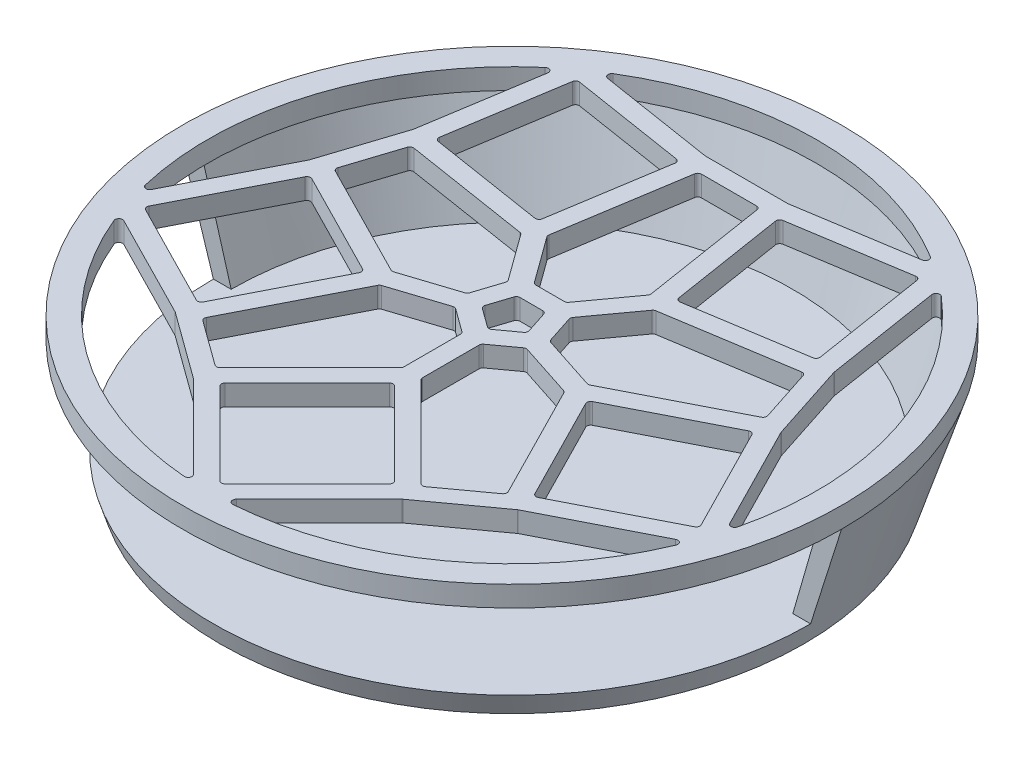
SolidWorks part; units mm, degrees
ref_plane "Plan de face" through (0, 0, 0) normal (0, 0, 1) x (1, 0, 0)
ref_plane "Plan de dessus" through (0, 0, 0) normal (0, 1, 0) x (1, 0, 0)
ref_plane "Plan de droite" through (0, 0, 0) normal (1, 0, 0) x (0, 0, -1)
ref_plane "Plan2" through (0, 2.75, 0) normal (0, 1, 0) x (1, 0, 0)
ref_plane "Plan3" through (0, 15.75, 0) normal (0, 1, 0) x (1, 0, 0)
sketch "Esquisse4" plane through (0, 0, 0) normal (0, 0, 1) x (1, 0, 0)
  line L0 (0, 0) -> (-39, 0)
  line L1 (-39, 0) -> (-44, 15.75)
  line L4 (-44, 15.75) -> (-44, 18.5)
  line L5 (-44, 18.5) -> (0, 18.5)
  line L7 (0, 0) -> (0, 18.5)
  dimension "D1" = 44
  dimension "D2" = 39
  dimension "D3" = 2.75
  dimension "D4" = 18.5
revolve "Révolution1" add sketch "Esquisse4" angle 360 about L7
sketch "Esquisse5" plane through (0, 2.75, 0) normal (0, 1, 0) x (1, 0, 0)
  line L8 (44, -44) -> (-44, -44)
  line L9 (37.5, 0) -> (44, 0)
  line L10 (44, 0) -> (44, -44)
  line L11 (-37.5, 0) -> (-44, 0)
  line L12 (-44, 0) -> (-44, -44)
  arc A0 (37.5, 0) -> (-37.5, 0) centre (0, 0) ccw
  circle A3 centre (0, 0) radius 44 construction
  dimension "D3" = 37.5
sketch "Esquisse6" plane through (0, 15.75, 0) normal (0, 1, 0) x (1, 0, 0)
  line L1 (-44, -44) -> (44, -44)
  line L3 (-41.25, 0) -> (-44, 0)
  line L4 (-44, 0) -> (-44, -44)
  line L5 (41.25, 0) -> (44, 0)
  line L6 (44, 0) -> (44, -44)
  arc A0 (41.25, 0) -> (-41.25, 0) centre (0, 0) ccw
  circle A1 centre (0, 0) radius 44 construction
  circle A2 centre (0, 0) radius 44 construction
  dimension "D3" = 41.25
loft "Enlèvement de matière-Lissage2" cut profiles "Esquisse5", "Esquisse6"
sketch "Esquisse7" plane through (0, 18.5, 0) normal (0, 1, 0) x (1, 0, 0)
  line L0 (0, -15.6655) -> (-11.6673, -27.3327)
  line L15 (-11.6673, -27.3327) -> (0, -39)
  line L16 (0, -39) -> (11.6673, -27.3327)
  line L17 (11.6673, -27.3327) -> (0, -15.6655)
  line L18 (0, -39) -> (0, -15.6655) construction
  line L19 (-11.6673, -27.3327) -> (11.6673, -27.3327) construction
  line L20 (-29.6004, 2.6499) -> (-37.0912, -12.0517)
  line L21 (-37.0912, -12.0517) -> (-22.3896, -19.5425)
  line L22 (-22.3896, -19.5425) -> (-14.8988, -4.8409)
  line L23 (-14.8988, -4.8409) -> (-29.6004, 2.6499)
  line L24 (-6.6268, 28.9705) -> (-22.9236, 31.5517)
  line L25 (-22.9236, 31.5517) -> (-25.5048, 15.2548)
  line L26 (-25.5048, 15.2548) -> (-9.2079, 12.6736)
  line L27 (-9.2079, 12.6736) -> (-6.6268, 28.9705)
  line L28 (25.5048, 15.2548) -> (22.9236, 31.5517)
  line L29 (22.9236, 31.5517) -> (6.6268, 28.9705)
  line L30 (6.6268, 28.9705) -> (9.2079, 12.6736)
  line L31 (9.2079, 12.6736) -> (25.5048, 15.2548)
  line L32 (22.3896, -19.5425) -> (37.0912, -12.0517)
  line L33 (37.0912, -12.0517) -> (29.6004, 2.6499)
  line L34 (29.6004, 2.6499) -> (14.8988, -4.8409)
  line L35 (14.8988, -4.8409) -> (22.3896, -19.5425)
  line L36 (0, 0) -> (0, -44) construction
  circle A0 centre (0, 0) radius 44 construction
  point P28 (0, 0)
  dimension "D2" = 5
  dimension "D1" = 16.5
extrude "Enlèv. mat.-Extru.3" cut sketch "Esquisse7" against normal up to next
sketch "Esquisse8" plane through (0, 18.5, 0) normal (0, 1, 0) x (1, 0, 0)
  line L2 (-20.3418, -21.0303) -> (-12.3388, -5.3235)
  line L3 (-12.3388, -5.3235) -> (-4.7304, -2.8513)
  line L17 (-26.287, 12.8475) -> (-8.8758, 10.0899)
  line L18 (-1.25, -5.3799) -> (-1.25, -13.3799)
  line L19 (-1.25, -13.3799) -> (-13.715, -25.845)
  line L20 (-13.715, -25.845) -> (-20.3418, -21.0303)
  line L21 (-13.1114, -2.9458) -> (-28.8182, 5.0572)
  line L22 (-28.8182, 5.0572) -> (-26.287, 12.8475)
  line L23 (-8.8758, 10.0899) -> (-4.1735, 3.6177)
  line L24 (-5.5029, -0.4737) -> (-13.1114, -2.9458)
  line L25 (4.0956, 28.9705) -> (6.8533, 11.5593)
  line L26 (-6.8533, 11.5593) -> (-4.0956, 28.9705)
  line L27 (-4.0956, 28.9705) -> (4.0956, 28.9705)
  line L28 (6.8533, 11.5593) -> (2.151, 5.0872)
  line L29 (-2.151, 5.0872) -> (-6.8533, 11.5593)
  line L31 (28.8182, 5.0572) -> (13.1114, -2.9458)
  line L41 (8.8758, 10.0899) -> (26.287, 12.8475)
  line L42 (2.151, 5.0872) -> (-2.151, 5.0872)
  line L43 (0, -15.6655) -> (-11.6673, -27.3327) construction
  line L44 (26.287, 12.8475) -> (28.8182, 5.0572)
  line L45 (13.1114, -2.9458) -> (5.5029, -0.4737)
  line L46 (4.1735, 3.6177) -> (8.8758, 10.0899)
  line L47 (13.715, -25.845) -> (1.25, -13.3799)
  line L48 (12.3388, -5.3235) -> (20.3418, -21.0303)
  line L49 (20.3418, -21.0303) -> (13.715, -25.845)
  line L50 (1.25, -13.3799) -> (1.25, -5.3799)
  line L51 (4.7304, -2.8513) -> (12.3388, -5.3235)
  line L52 (-22.3896, -19.5425) -> (-14.8988, -4.8409) construction
  line L53 (5.5029, -0.4737) -> (4.1735, 3.6177)
  line L54 (-22.3072, 33.9852) -> (-5.5125, 31.3252)
  line L55 (-5.5125, 31.3252) -> (5.5125, 31.3252)
  line L56 (5.5125, 31.3252) -> (22.3072, 33.9852)
  line L57 (-6.6268, 28.9705) -> (-22.9236, 31.5517) construction
  line L58 (22.9236, 31.5517) -> (6.6268, 28.9705) construction
  line L59 (0, 28.9705) -> (0, 30.6305) construction
  line L60 (-8.8758, 10.0899) -> (-5.5125, 31.3252) construction
  line L61 (-9.2079, 12.6736) -> (-6.6268, 28.9705) construction
  line L62 (31.4955, 4.4373) -> (39.2151, -10.7134)
  line L63 (25.4285, 31.7174) -> (28.0886, 14.9227)
  line L64 (28.0886, 14.9227) -> (31.4955, 4.4373)
  line L65 (13.9528, -28.5827) -> (1.9291, -40.6064)
  line L66 (38.0229, -14.3828) -> (22.8721, -22.1024)
  line L67 (22.8721, -22.1024) -> (13.9528, -28.5827)
  line L68 (-22.8721, -22.1024) -> (-38.0229, -14.3828)
  line L69 (-1.9291, -40.6064) -> (-13.9528, -28.5827)
  line L70 (-13.9528, -28.5827) -> (-22.8721, -22.1024)
  line L71 (-28.0886, 14.9227) -> (-25.4285, 31.7174)
  line L72 (-39.2151, -10.7134) -> (-31.4955, 4.4373)
  line L73 (-31.4955, 4.4373) -> (-28.0886, 14.9227)
  line L74 (1.25, -5.3799) -> (4.7304, -2.8513)
  line L75 (-4.7304, -2.8513) -> (-1.25, -5.3799)
  line L76 (-4.1735, 3.6177) -> (-5.5029, -0.4737)
  arc A0 (22.3072, 33.9852) -> (-22.3072, 33.9852) centre (0, 0) ccw
  arc A1 (39.2151, -10.7134) -> (25.4285, 31.7174) centre (0, 0) ccw
  arc A2 (1.9291, -40.6064) -> (38.0229, -14.3828) centre (0, 0) ccw
  arc A3 (-38.0229, -14.3828) -> (-1.9291, -40.6064) centre (0, 0) ccw
  arc A4 (-25.4285, 31.7174) -> (-39.2151, -10.7134) centre (0, 0) ccw
  point P3 (0, 0)
  point P12 (1.25, -5.3799)
  point P31 (0, 0)
  point P62 (0, 0)
  point P63 (-7.6663, 0)
  point P64 (0, 0)
  point P72 (0, 0)
  point P73 (0, 0)
  dimension "D7" = 40.6522
  dimension "D2" = 2.5
  dimension "D3" = 5
  dimension "D1" = 2.5
  dimension "D4" = 2.5
  dimension "D5" = 2.5
  dimension "D8" = 8
  dimension "D10" = 8
  dimension "D11" = 4.302
  dimension "D6" = 5
  dimension "D9" = 5
extrude "Enlèv. mat.-Extru.4" cut sketch "Esquisse8" against normal up to surface (2.75 mm away) up to face at (25.995, 15.75, 8.4463)
sketch "Esquisse9" plane through (0, 18.5, 0) normal (0, 1, 0) x (1, 0, 0)
  line L0 (-1.25, -5.3799) -> (-4.7304, -2.8513) construction
  line L1 (-1.8797, 2.5872) -> (-3.0414, -0.9882)
  line L2 (-3.0414, -0.9882) -> (0, -3.198)
  line L3 (0, -3.198) -> (3.0414, -0.9882)
  line L4 (3.0414, -0.9882) -> (1.8797, 2.5872)
  line L5 (1.8797, 2.5872) -> (-1.8797, 2.5872)
  circle A1 centre (0, 0) radius 2.5872 construction
  point P1 (0, -3.8866)
  dimension "D1" = 2.5
extrude "Enlèv. mat.-Extru.5" cut sketch "Esquisse9" against normal up to surface (2.75 mm away) up to face at (8.9377, 15.75, 12.3016)
fillet "Congé2" radius 0.5 75 edges at (-6.8533, 17.125, -11.5593) (9.2079, 17.125, -12.6736) (14.8988, 17.125, 4.8409) (22.3896, 17.125, 19.5425) (13.715, 17.125, 25.845) (1.25, 17.125, 13.3799) (-22.3896, 17.125, 19.5425) (-14.8988, 17.125, 4.8409) (28.8182, 17.125, -5.0572) (37.0912, 17.125, 12.0517) (20.3418, 17.125, 21.0303) (11.6673, 17.125, 27.3327) (-13.715, 17.125, 25.845) (-11.6673, 17.125, 27.3327) (-20.3418, 17.125, 21.0303) (-37.0912, 17.125, 12.0517) (-28.8182, 17.125, -5.0572) (-25.5048, 17.125, -15.2548) (0, 17.125, 15.6655) (6.6268, 17.125, -28.9705) (-26.287, 17.125, -12.8475) (-29.6004, 17.125, -2.6499) (-22.9236, 17.125, -31.5517) (-12.3388, 17.125, 5.3235) (12.3388, 17.125, 5.3235) (8.8758, 17.125, -10.0899) (-4.0956, 17.125, -28.9705) (29.6004, 17.125, -2.6499) (-8.8758, 17.125, -10.0899) (4.0956, 17.125, -28.9705) (26.287, 17.125, -12.8475) (22.9236, 17.125, -31.5517) (0, 17.125, 39) (-1.25, 17.125, 13.3799) (25.5048, 17.125, -15.2548) (6.8533, 17.125, -11.5593) (13.1114, 17.125, 2.9458) (-13.1114, 17.125, 2.9458) (-9.2079, 17.125, -12.6736) (-6.6268, 17.125, -28.9705) (1.9291, 17.125, 40.6064) (-1.9291, 17.125, 40.6064) (-38.0229, 17.125, 14.3828) (-39.2151, 17.125, 10.7134) (-25.4285, 17.125, -31.7174) (-22.3072, 17.125, -33.9852) (38.0229, 17.125, 14.3828) (22.3072, 17.125, -33.9852) (-13.9528, 17.125, 28.5827) (-22.8721, 17.125, 22.1024) (13.9528, 17.125, 28.5827) (22.8721, 17.125, 22.1024) (-31.4955, 17.125, -4.4373) (-28.0886, 17.125, -14.9227) (5.5125, 17.125, -31.3252) (-5.5125, 17.125, -31.3252) (39.2151, 17.125, 10.7134) (31.4955, 17.125, -4.4373) (25.4285, 17.125, -31.7174) (28.0886, 17.125, -14.9227) (3.0414, 17.125, 0.9882) (0, 17.125, 3.198) (-3.0414, 17.125, 0.9882) (1.8797, 17.125, -2.5872) (-1.8797, 17.125, -2.5872) (-4.7304, 17.125, 2.8513) (-1.25, 17.125, 5.3799) (-4.1735, 17.125, -3.6177) (-5.5029, 17.125, 0.4737) (2.151, 17.125, -5.0872) (-2.151, 17.125, -5.0872) (4.1735, 17.125, -3.6177) (5.5029, 17.125, 0.4737) (4.7304, 17.125, 2.8513) (1.25, 17.125, 5.3799)
